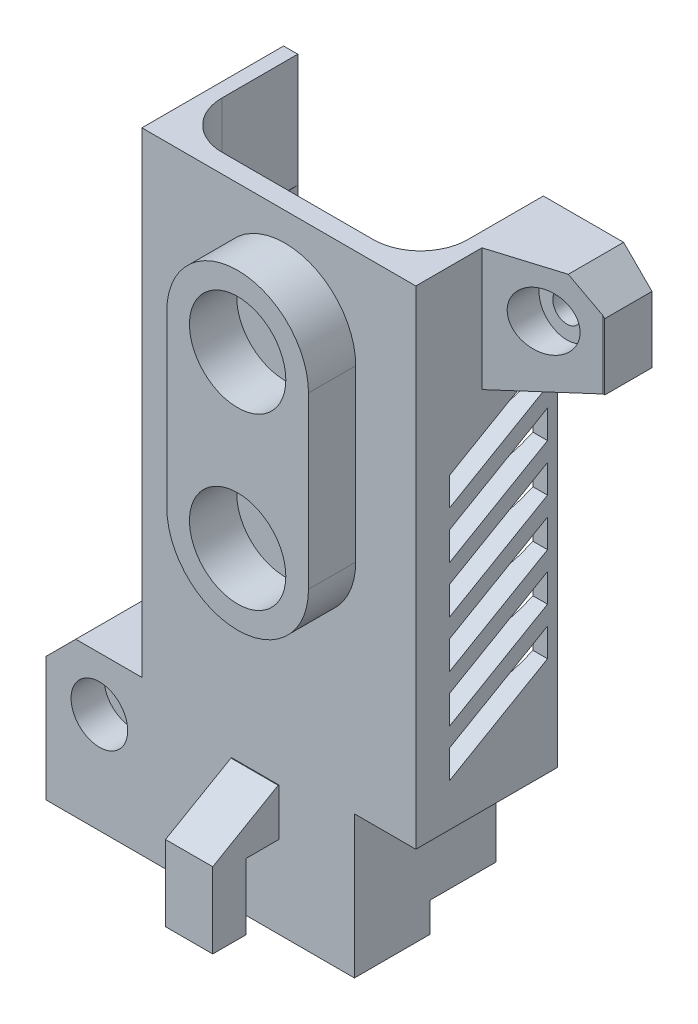
SolidWorks part; units mm, degrees
ref_plane "Přední rovina" through (0, 0, 0) normal (0, 0, 1) x (1, 0, 0)
ref_plane "Horní rovina" through (0, 0, 0) normal (0, 1, 0) x (1, 0, 0)
ref_plane "Pravá rovina" through (0, 0, 0) normal (1, 0, 0) x (0, 0, -1)
sketch "Skica2" plane through (0, 0, 0) normal (0, -1, 0) x (1, 0, 0)
  line L0 (8, 0) -> (6, 0)
  line L1 (-6, 0) -> (-8, 0)
  circle A0 centre (0, 0) radius 8 construction
  circle A1 centre (0, 0) radius 6 construction
  arc A2 (8, 0) -> (-8, 0) centre (0, 0) ccw
  arc A3 (6, 0) -> (-6, 0) centre (0, 0) ccw
extrude "Přidat vysunutím1" add sketch "Skica2" along normal up to surface (6 mm away)
sketch "Skica3" plane through (0, -9.7, 0) normal (0, -1, 0) x (1, 0, 0)
  line L0 (8, 0) -> (4.5, 0)
  line L1 (-4.5, 0) -> (-8, 0)
  line L2 (8, 0) -> (2, 0)
  line L3 (-2, 0) -> (-8, 0)
  circle A1 centre (0, 0) radius 8
  arc A2 (8, 0) -> (-8, 0) centre (0, 0) ccw
  arc A4 (2, 0) -> (-2, 0) centre (0, 0) ccw
  circle M2 centre (0, 0) radius 4.5
  circle M3 centre (0, 0) radius 8
  dimension "D1" = 0
extrude "Přidat vysunutím2" add sketch "Skica3" along normal up to surface (4 mm away) separate body contours A4 L2 L3 M2 | L1 L0 M2 M3
sketch "Skica4" plane through (0, 0, 0) normal (0, 0, -1) x (-1, 0, 0)
  circle A0 centre (-7.768, -14.6856) radius 4.1255
sketch "Skica6" plane through (0, -13.7, 0) normal (0, -1, 0) x (1, 0, 0)
  line L0 (-13, 0) -> (-8, 0)
  line L1 (8, 0) -> (13, 0)
  arc A0 (8, 0) -> (-8, 0) centre (0, 0) ccw construction
  arc A1 (8, 0) -> (-8, 0) centre (0, 0) ccw
  arc A2 (13, 0) -> (-13, 0) centre (0, 0) ccw
extrude "Přidat vysunutím3" add sketch "Skica6" against normal up to surface (18.7 mm away)
sketch "Skica7" plane through (0, 5, 0) normal (0, 1, 0) x (1, 0, 0)
  line L0 (-13, 0) -> (-14.5, 0)
  line L1 (-14.5, 0) -> (-14.5, -15)
  line L2 (-14.5, -15) -> (14.5, -15)
  line L3 (14.5, -15) -> (14.5, 0)
  line L4 (14.5, 0) -> (13, 0)
  arc A1 (-13, 0) -> (13, 0) centre (0, 0) ccw
extrude "Přidat vysunutím4" add sketch "Skica7" along normal up to surface (36 mm away) separate body
sketch "Skica8" plane through (0, 41, 0) normal (0, 1, 0) x (1, 0, 0)
  line L0 (-14.5, 0) -> (-13, 0) construction
  line L1 (13, 0) -> (21.5, 0) construction
  line L3 (-14.5, -15) -> (-14.5, 0) construction
  line L4 (14.5, -15) -> (-14.5, -15) construction
  line L5 (-14.5, 0) -> (-13, 0)
  line L6 (13, 0) -> (14.5, 0)
  line L7 (14.5, 0) -> (14.5, -15)
  line L8 (-14.5, -15) -> (-14.5, 0)
  line L9 (14.5, -15) -> (-14.5, -15)
  line L10 (-13, 0) -> (-13, -8)
  line L11 (-8, -13) -> (8, -13)
  line L12 (13, -8) -> (13, 0)
  arc A0 (-13, 0) -> (13, 0) centre (0, 0) ccw construction
  arc A1 (-13, -8) -> (-8, -13) centre (-8, -8) ccw
  arc A2 (8, -13) -> (13, -8) centre (8, -8) ccw
  dimension "D1" = 5
extrude "Přidat vysunutím5" add sketch "Skica8" along normal up to surface (12 mm away)
sketch "Skica9" plane through (0, 5, 0) normal (0, -1, 0) x (1, 0, 0)
  line L5 (13, 0) -> (14.5, 0)
  line L6 (14.5, 0) -> (14.5, 15)
  line L7 (14.5, 15) -> (-14.5, 15)
  line L8 (-14.5, 15) -> (-14.5, 0)
  line L9 (-14.5, 0) -> (-13, 0)
  line L10 (13, 0) -> (14.5, 0)
  line L11 (14.5, 0) -> (14.5, 15)
  line L12 (14.5, 15) -> (-14.5, 15)
  line L13 (-14.5, 15) -> (-14.5, 0)
  line L14 (-14.5, 0) -> (-13, 0)
  arc A1 (13, 0) -> (-13, 0) centre (0, 0) ccw
  arc A2 (13, 0) -> (-13, 0) centre (0, 0) ccw
  dimension "D1" = 0
extrude "Přidat vysunutím6" add sketch "Skica9" along normal up to surface (18.7 mm away) up to face at (0, -13.7, 3.75)
sketch "Skica10" plane through (0, 0, 0) normal (0, 0, -1) x (-1, 0, 0)
  line L0 (-14.5, -13.7) -> (-14.5, 53) construction
  line L1 (-14.5, 1.3549) -> (-8, 1.3549)
  line L2 (-14.5, 1.3549) -> (-14.5, -14.6856)
  line L3 (-14.5, -14.6856) -> (-8, -14.6856)
  line L4 (-8, 1.3549) -> (-8, -14.6856)
  line L5 (-14.5, 1.3549) -> (-8.0034, 1.3549) construction
  line L6 (-8, -6) -> (-8, -9.7) construction
extrude "Odebrat vysunutím2" cut sketch "Skica10" against normal up to surface (15 mm away) up to face at (0, 19.65, 15)
extrude "Odebrat vysunutím3" cut sketch "Skica4" against normal blind 7
sketch "Skica11" plane through (0, 0, 0) normal (0, 0, 1) x (1, 0, 0)
  line L17 (-24.65, -13.7) -> (-14.5, -13.7)
  line L18 (-14.5, -13.7) -> (-4.7569, -13.7)
  line L19 (-2.2431, -13.7) -> (-2, -13.7)
  line L20 (-2, -13.7) -> (-2, -9.7)
  line L21 (-2, -9.7) -> (-8, -9.7)
  line L22 (-8, -9.7) -> (-8, -6)
  line L23 (-8, -6) -> (-6, -6)
  line L24 (-6, -6) -> (-6, 0)
  line L25 (-6, 0) -> (-8, 0)
  line L26 (-8, 0) -> (-8, 5)
  line L27 (-8, 5) -> (-13, 5)
  line L28 (-13, 5) -> (-13, 10.9652)
  line L29 (-13, 10.9652) -> (-14.5, 10.9652)
  line L30 (-14.5, 10.9652) -> (-14.5, 2.6106)
  line L31 (-14.5, 2.6106) -> (-21.5034, 2.6106)
  line L32 (-21.5034, 2.6106) -> (-24.65, -0.5361)
  line L33 (-24.65, -0.5361) -> (-24.65, -13.7)
  line L34 (-24.65, -13.7) -> (-14.5, -13.7)
  line L35 (-14.5, -13.7) -> (-4.7569, -13.7)
  line L36 (-2.2431, -13.7) -> (-2, -13.7)
  line L37 (-2, -13.7) -> (-2, -9.7)
  line L38 (-2, -9.7) -> (-8, -9.7)
  line L39 (-8, -9.7) -> (-8, -6)
  line L40 (-8, -6) -> (-6, -6)
  line L41 (-6, -6) -> (-6, 0)
  line L42 (-6, 0) -> (-8, 0)
  line L43 (-8, 0) -> (-8, 5)
  line L44 (-8, 5) -> (-13, 5)
  line L45 (-13, 5) -> (-13, 10.9652)
  line L46 (-13, 10.9652) -> (-14.5, 10.9652)
  line L47 (-14.5, 10.9652) -> (-14.5, 2.6106)
  line L48 (-14.5, 2.6106) -> (-21.5034, 2.6106)
  line L49 (-21.5034, 2.6106) -> (-24.65, -0.5361)
  line L50 (-24.65, -0.5361) -> (-24.65, -13.7)
  arc A1 (-2.2431, -13.7) -> (-4.7569, -13.7) centre (-3.5, -18.5394) ccw
  arc A2 (-2.2431, -13.7) -> (-4.7569, -13.7) centre (-3.5, -18.5394) ccw
  circle A3 centre (-19, -3.0394) radius 1.6
  dimension "D1" = 0
extrude "Přidat vysunutím7" add sketch "Skica11" along normal up to surface (15 mm away) up to face at (2.6667, 13.5516, 15)
sketch "Skica12" plane through (0, 0, 0) normal (0, 0, -1) x (-1, 0, 0)
  circle A0 centre (3.5, -18.5394) radius 5
  dimension "D1" = 10
extrude "Odebrat vysunutím4" cut sketch "Skica12" against normal blind 10
sketch "Skica13" plane through (0, 0, 15) normal (0, 0, 1) x (1, 0, 0)
  circle A0 centre (-19, -3.0394) radius 3
  dimension "D1" = 6
extrude "Odebrat vysunutím5" cut sketch "Skica13" against normal blind 3.5
sketch "Skica14" plane through (14.5, 0, 0) normal (1, 0, 0) x (0, 0, -1)
  line L0 (-11.4494, 13.8487) -> (-1.0571, 19.8487)
  line L10 (-11.4494, 8.8487) -> (-1.0571, 14.8487)
  line L11 (-11.4494, 5.8487) -> (-11.4494, 8.8487)
  line L12 (-1.0571, 11.8487) -> (-11.4494, 5.8487)
  line L13 (-1.0571, 14.8487) -> (-1.0571, 11.8487)
  line L14 (-1.0571, 19.8487) -> (-1.0571, 16.8487)
  line L15 (-1.0571, 16.8487) -> (-11.4494, 10.8487)
  line L16 (-11.4494, 10.8487) -> (-11.4494, 13.8487)
  line L17 (-11.4494, 18.8487) -> (-1.0571, 24.8487)
  line L18 (-1.0571, 24.8487) -> (-1.0571, 21.8487)
  line L19 (-1.0571, 21.8487) -> (-11.4494, 15.8487)
  line L20 (-11.4494, 15.8487) -> (-11.4494, 18.8487)
  line L21 (-11.4494, 23.8487) -> (-1.0571, 29.8487)
  line L22 (-1.0571, 29.8487) -> (-1.0571, 26.8487)
  line L23 (-1.0571, 26.8487) -> (-11.4494, 20.8487)
  line L24 (-11.4494, 20.8487) -> (-11.4494, 23.8487)
  line L25 (-11.4494, 28.8487) -> (-1.0571, 34.8487)
  line L26 (-1.0571, 34.8487) -> (-1.0571, 31.8487)
  line L27 (-1.0571, 31.8487) -> (-11.4494, 25.8487)
  line L28 (-11.4494, 25.8487) -> (-11.4494, 28.8487)
  line L29 (-11.4494, 33.8487) -> (-1.0571, 39.8487)
  line L30 (-1.0571, 39.8487) -> (-1.0571, 36.8487)
  line L31 (-1.0571, 36.8487) -> (-11.4494, 30.8487)
  line L32 (-11.4494, 30.8487) -> (-11.4494, 33.8487)
  dimension "D1" = 6
extrude "Odebrat vysunutím6" cut sketch "Skica14" against normal up to surface (8.3428 mm away)
sketch "Skica15" plane through (-14.5, 0, 0) normal (-1, 0, 0) x (0, 0, 1)
  line L0 (0, 10.9652) -> (0, 36.9652) construction
  circle A0 centre (-12, 35.9652) radius 1.5 construction
  circle A1 centre (-12, 11.9652) radius 1.5 construction
  arc A2 (0, 36.9652) -> (0, 10.9652) centre (0, 23.9652) ccw construction
  circle A6 centre (12, 35.9652) radius 1.5
  circle A7 centre (12, 11.9652) radius 1.5
extrude "Odebrat vysunutím7" cut sketch "Skica15" against normal up to surface (8 mm away)
sketch "Skica16" plane through (-14.5, 0, 0) normal (-1, 0, 0) x (0, 0, 1)
  line L0 (0, 10.9652) -> (0, 36.9652) construction
  arc A0 (0, 36.9652) -> (0, 10.9652) centre (0, 23.9652) ccw construction
  circle A1 centre (0, 23.9652) radius 13
extrude "Odebrat vysunutím8" cut sketch "Skica16" against normal up to surface (14.5 mm away)
sketch "Skica17" plane through (14.5, 0, 0) normal (1, 0, 0) x (0, 0, -1)
  line L1 (0, 53) -> (-5, 53)
  line L2 (0, 53) -> (0, 43)
  line L3 (0, 43) -> (-5, 43)
  line L4 (-5, 53) -> (-5, 43)
  dimension "D1" = 10
  dimension "D2" = 5
extrude "Přidat vysunutím8" add sketch "Skica17" along normal blind 10
chamfer "Zkosení1" distance 3 angle 73 1 edges at (14.5, 43, 2.5)
chamfer "Zkosení2" distance 3 angle 73 1 edges at (14.5, 46.5, 5)
sketch "Skica18" plane through (0, 0, 0) normal (0, 0, -1) x (-1, 0, 0)
  line L0 (-24.5, 43) -> (-24.3126, 43) construction
  line L1 (-24.5, 53) -> (-14.5, 53) construction
  line L2 (-24.5, 53) -> (-24.5, 43) construction
  line L3 (-24.5, 43) -> (-14.5, 43) construction
  line L4 (-14.5, 53) -> (-14.5, 43) construction
  line L5 (-14.5, 53) -> (-24.5, 43) construction
  circle A0 centre (-19.5, 48) radius 1.5
  dimension "D2" = 3
  dimension "D1" = 10
extrude "Odebrat vysunutím9" cut sketch "Skica18" against normal blind 4
sketch "Skica19" plane through (0, 0, 4) normal (0, 0, -1) x (-1, 0, 0)
  circle A0 centre (-19.5, 48) radius 2.9551
extrude "Odebrat vysunutím10" cut sketch "Skica19" against normal blind 4
chamfer "Zkosení3" distance 3 angle 45 1 edges at (24.5, 53, 2.5)
sketch "Skica20" plane through (0, 0, 15) normal (0, 0, 1) x (1, 0, 0)
  line L1 (0, 0) -> (-5, 0)
  line L2 (0, 0) -> (0, -5)
  line L3 (0, -5) -> (-5, -5)
  line L4 (-5, 0) -> (-5, -5)
  dimension "D1" = 5
extrude "Přidat vysunutím9" add sketch "Skica20" along normal blind 7
sketch "Skica21" plane through (0, -5, 0) normal (0, -1, 0) x (1, 0, 0)
  line L0 (0, 22) -> (0, 15) construction
  line L1 (-5, 22) -> (0, 22)
  line L2 (-5, 22) -> (-5, 18.5)
  line L3 (-5, 18.5) -> (0, 18.5)
  line L4 (0, 22) -> (0, 18.5)
extrude "Přidat vysunutím10" add sketch "Skica21" along normal blind 7
chamfer "Zkosení4" distance 4 angle 60 1 edges at (-2.5, 0, 22)
sketch "Skica22" plane through (0, 0, 15) normal (0, 0, 1) x (1, 0, 0)
  line L0 (0.6352, 24.505) -> (0.6352, 42.505) construction
  line L1 (-6.8648, 24.505) -> (-6.8648, 42.505)
  line L2 (8.1352, 24.505) -> (8.1352, 42.505)
  circle A0 centre (0.6352, 42.505) radius 5.1
  circle A1 centre (0.6352, 24.505) radius 5.1
  arc A3 (-6.8648, 24.505) -> (8.1352, 24.505) centre (0.6352, 24.505) ccw
  arc A4 (8.1352, 42.505) -> (-6.8648, 42.505) centre (0.6352, 42.505) ccw
  point P4 (0.6352, 33.505)
  dimension "D1" = 10.2
  dimension "D2" = 7.5
  dimension "D3" = 18
extrude "Přidat vysunutím11" add sketch "Skica22" along normal blind 5
